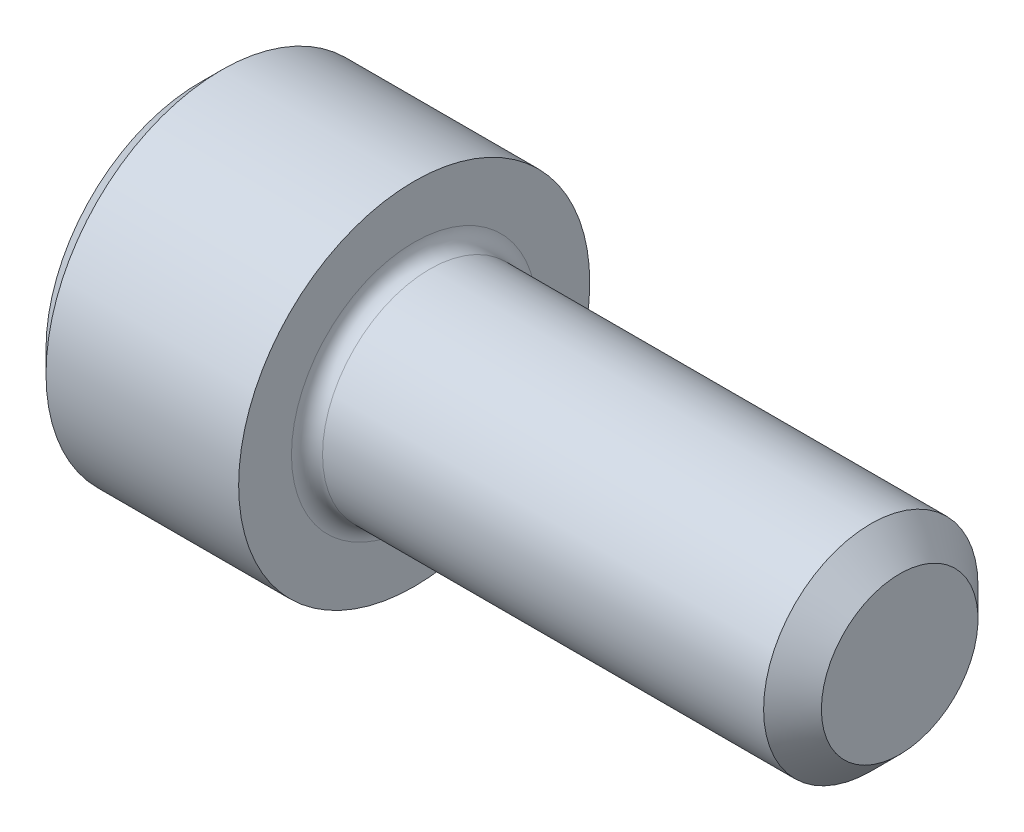
SolidWorks part; units mm, degrees
revolve "Base-Revolve" add sketch "BodySke"
sketch "BodySke" plane through (0, 0, 0) normal (0, 0, 1) x (1, 0, 0)
  line L0 (0, 0) -> (0, 2.5146)
  line L1 (0.3556, 2.8702) -> (3.5052, 2.8702)
  line L2 (3.5052, 2.8702) -> (3.5052, 1.7526)
  line L3 (3.5052, 1.7526) -> (10.9703, 1.7526)
  line L4 (11.4427, 1.2802) -> (11.4427, 0)
  line L5 (11.4427, 0) -> (0, 0)
  line L6 (-31.75, 0) -> (127, 0) construction
  line L7 (0, 2.5146) -> (0.3556, 2.8702)
  line L8 (11.4427, 1.2802) -> (10.9703, 1.7526)
  line L9 (0, -2.5146) -> (0.3556, -2.8702) construction
  line L10 (11.4427, -1.2802) -> (10.9703, -1.7526) construction
  line L11 (4.2977, 9.525) -> (4.2977, 3.175) construction
  line L12 (3.5052, 9.525) -> (3.5052, 3.175) construction
  line L13 (-26.6573, 9.525) -> (-26.6573, 3.175) construction
  dimension "Diameter" = 3.5052
  dimension "Head_ht" = 3.5052
  dimension "Length" = 7.9375
  dimension "Body_ch_ang" = 45
  dimension "Head_dia" = 5.7404
  dimension "Head_ch_ang" = 45
  dimension "Head_side_ht" = 3.1496
  dimension "Minor_dia" = 2.5603
  dimension "Advance" = 0.7925
  dimension "Thread_nom" = 7.9375
  dimension "Thread_length" = 38.1
cosmetic thread "ThreadCosmetic"
fillet "Fillet1" radius 0.254 1 edges at (3.5052, 0, 1.7526)
other "Defeature"
material "Alloy Steel"
ref_plane "Plane1" through (0, 0, 0) normal (0, 0, 1) x (1, 0, 0)
ref_plane "Plane2" through (0, 0, 0) normal (0, 1, 0) x (1, 0, 0)
ref_plane "Plane3" through (0, 0, 0) normal (1, 0, 0) x (0, 0, -1)
sketch "Sketch2" plane through (0, 0, 0) normal (0, 0, 1) x (1, 0, 0)
  line L0 (0, 1.3843) -> (1.6256, 1.3843)
  line L1 (1.6256, 1.3843) -> (2.4248, 0)
  line L2 (-31.75, 0) -> (127, 0) construction
  line L3 (2.4248, 0) -> (0, 0)
  line L4 (0, 0) -> (0, 1.3843)
  line L5 (0, 2.5146) -> (0, -2.5146) construction
  line L6 (0, 0) -> (47.625, 0) construction
  line L7 (3.5052, -2.8702) -> (3.5052, 2.8702) construction
  dimension "D1" = 1.3843
  dimension "D2" = 60
revolve "Hex-PreBroach" cut sketch "Sketch2" angle 360 about L6
sketch "Sketch3" plane through (0, 0, 0) normal (-1, 0, 0) x (0, 0.5, 0.866)
  line L0 (0.7992, 1.3843) -> (-0.7992, 1.3843)
  line L1 (-0.7992, 1.3843) -> (-1.5985, 0)
  line L2 (0.7992, 1.3843) -> (1.5985, 0)
  line L3 (0.7992, -1.3843) -> (1.5985, 0)
  line L4 (0.7992, -1.3843) -> (-0.7992, -1.3843)
  line L5 (-0.7992, -1.3843) -> (-1.5985, 0)
  dimension "D1" = 1.3843
  dimension "D2" = 1.3843
  dimension "Hex_size" = 2.7686
extrude "Hex" cut sketch "Sketch3" against normal blind 1.6256
sketch "Sketch4" plane through (0, 0, 0) normal (-1, 0, 0) x (0, 0, 1)
  line L0 (0, 0) -> (1.7399, 0)
  line L1 (0, 0) -> (6.1484, 3.5498) construction
  line L2 (0, 0) -> (0.8699, 1.5068)
  line L3 (1.4457, 0.3947) -> (1.6607, 0.5189)
  line L4 (1.0647, 1.0546) -> (1.2797, 1.1788)
  arc A0 (1.4457, 0.3947) -> (1.0647, 1.0546) centre (0, 0) ccw
  arc A1 (1.7399, 0) -> (1.6607, 0.5189) centre (0, 0) ccw
  arc A2 (0.8699, 1.5068) -> (1.2797, 1.1788) centre (0, 0) cw
  dimension "D1" = 30
  dimension "D2" = 60
  dimension "Spline_p_dim" = 0.762
  dimension "D3" = 0.381
extrude "Spline" [suppressed] cut sketch "Sketch4" against normal blind 1.6256
pattern_circular "CirPattern1" [suppressed] count 6 every 60
sketch "Sketch5" plane through (0, 0, 0) normal (0, 0, 1) x (1, 0, 0)
  line L0 (-31.75, 0) -> (127, 0) construction
  line L2 (0, 2.5146) -> (0, -2.5146) construction
  circle A0 centre (1.27, 0) radius 0.4445
  dimension "Drilled_hole_dia" = 0.889
  dimension "Drilled_hole_loc" = 1.27
extrude "Hole" [suppressed] cut sketch "Sketch5" against normal through all and the other way through all
pattern_circular "Drilled-4" [suppressed] count 2 every 60
pattern_circular "Drilled-6" [suppressed] count 3 every 60
sketch "ThdSchSke" plane through (0, 0, 0) normal (0, 0, 1) x (1, 0, 0)
  line L0 (4.2977, -1.2802) -> (3.9669, -1.7526)
  line L1 (4.2977, -1.2802) -> (4.6285, -1.7526)
  line L2 (4.6285, -1.7526) -> (4.6285, -2.1908)
  line L3 (-3.175, 0) -> (5.1513, 0) construction
  line L5 (4.6285, -2.1908) -> (3.9669, -2.1908)
  line L6 (3.9669, -2.1908) -> (3.9669, -1.7526)
  line L7 (0, 2.5146) -> (0, -2.5146) construction
  dimension "Thread_minor" = 2.5603
  dimension "Diameter" = 3.5052
  dimension "Start" = 4.2977
revolve "ThreadSchematic" [suppressed] cut sketch "ThdSchSke" angle 360 about L3
pattern_linear "ThdSchPat" [suppressed]
equation "\"D2@Sketch3\" = \"Hex_size@Sketch3\" / 2"
equation "\"D1@Sketch3\" = \"Hex_size@Sketch3\" / 2"
equation "\"D1@Sketch2\" = \"Hex_size@Sketch3\" / 2"
equation "\"D3@Sketch4\" = \"Spline_p_dim@Sketch4\" / 2"
equation "\"Thread_minor@ThreadCosmetic\"  =  \"Minor_dia@BodySke\""
equation "\"D2@CirPattern1\" = 360 / \"Num_teeth@CirPattern1\""
equation "\"Wall_thickness@Sketch2\" = \"Head_ht@BodySke\" - \"Key_eng@Hex\""
equation "\"Thread_length@ThreadCosmetic\" = ((sgn( (\"Length@BodySke\" - \"Advance@BodySke\" ) - \"Thread_nom@BodySke\" )-1)*( (\"Length@BodySke\" - \"Advance@BodySke\" ) - \"Thread_nom@BodySke\" ))/-2+ \"Thread_nom@BodySke\""
equation "\"Thread_minor@ThdSchSke\" = \"Minor_dia@BodySke\""
equation "\"Diameter@ThdSchSke\" = \"Diameter@BodySke\""
equation "\"Overcut@ThdSchSke\" = \"Diameter@BodySke\" * 1.25"
equation "\"Start@ThdSchSke\" = \"Head_ht@BodySke\" + \"Length@BodySke\" - \"Thread_length@ThreadCosmetic\"  '---Non-countersunk---"
equation "\"Num_threads@ThdSchPat\" = int( \"Thread_length@ThreadCosmetic\" / \"Advance@BodySke\" + 0.999 )  + 1"
equation "\"Advance@ThdSchPat\" = \"Thread_length@ThreadCosmetic\" /  (\"Num_threads@ThdSchPat\" - 1) 'relax it"
equation "\"Num_threads@ThdSchPat\" = \"Num_threads@ThdSchPat\" - sgn( \"Num_threads@ThdSchPat\" - 1) '---chamfered tips only---"
